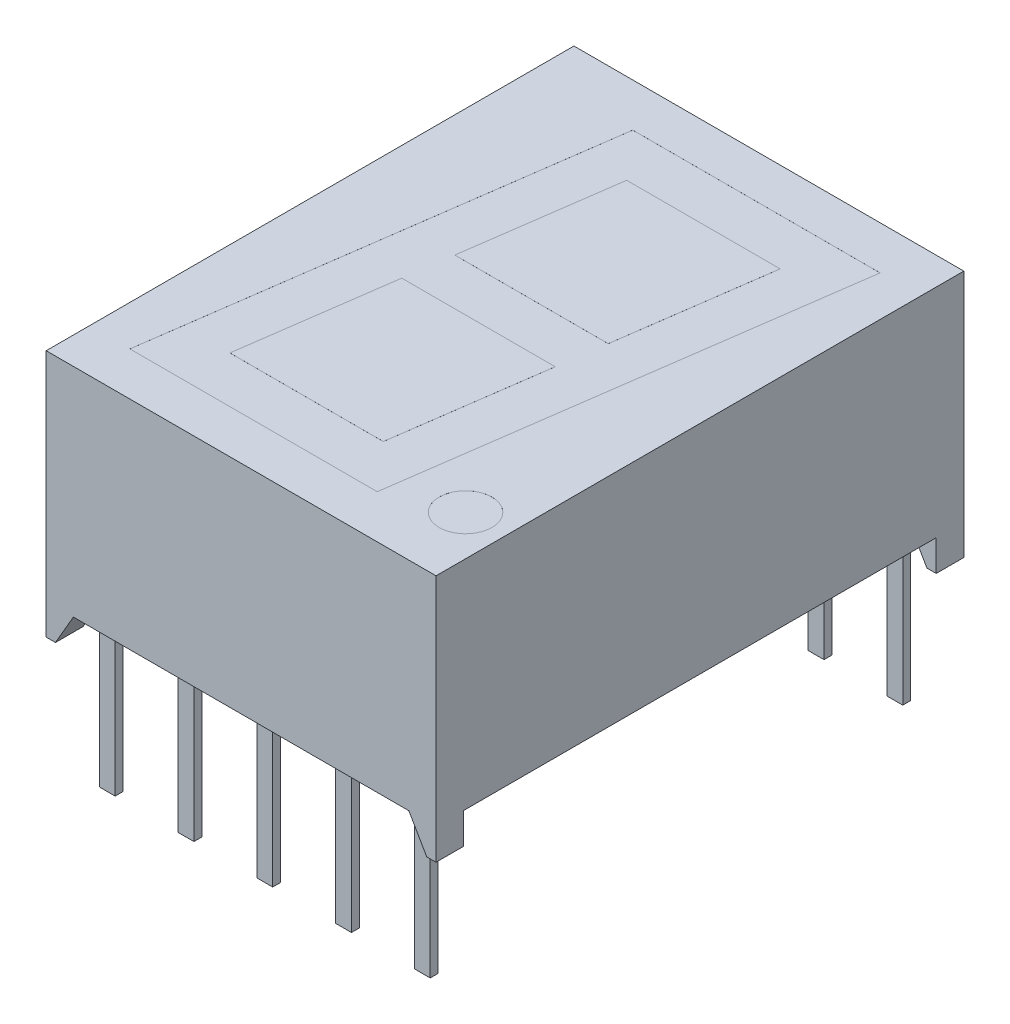
SolidWorks part; units mm, degrees
ref_plane "Plane1" through (0, 0, 0) normal (0, 0, 1) x (1, 0, 0)
ref_plane "Plane2" through (0, 0, 0) normal (0, 1, 0) x (1, 0, 0)
ref_plane "Plane3" through (0, 0, 0) normal (1, 0, 0) x (0, 0, -1)
sketch "Sketch1" plane through (0, 0, 0) normal (1, 0, 0) x (0, 0, -1)
  line L0 (0, 0) -> (0, -7) construction
  line L1 (-8.51, 0) -> (8.51, 0)
  line L2 (-8.51, 0) -> (-8.51, -8)
  line L3 (-8.51, -8) -> (-7.62, -8)
  line L4 (8.51, 0) -> (8.51, -8)
  line L5 (7.62, -8) -> (8.51, -8)
  line L6 (-7.62, -8) -> (-7.62, -7)
  line L7 (-7.62, -7) -> (7.62, -7)
  line L8 (7.62, -8) -> (7.62, -7)
  dimension "D1" = 17.02
  dimension "D2" = 8
  dimension "D3" = 15.24
  dimension "D4" = 1
extrude "Extrude1" add sketch "Sketch1" along normal mid plane 12.573
sketch "Sketch4" plane through (0, 0, 0) normal (0, 1, 0) x (-1, 0, 0)
  line L0 (6.2865, 0) -> (3.9888, 0) construction
  line L1 (6.2865, -8.51) -> (6.2865, 8.51) construction
  line L2 (4.9881, 7.11) -> (2.9896, -7.11)
  line L3 (2.9896, -7.11) -> (-4.9881, -7.11)
  line L4 (-4.9881, -7.11) -> (-2.9896, 7.11)
  line L5 (-2.9896, 7.11) -> (4.9881, 7.11)
  line L6 (3.9888, 0) -> (-3.9888, 0) construction
  line L7 (0, 0) -> (0, 11.7148) construction
  line L8 (-1.6856, 5.61) -> (3.2625, 5.61)
  line L9 (-3.2625, -5.61) -> (-2.5795, -0.75)
  line L10 (1.6856, -5.61) -> (-3.2625, -5.61)
  line L11 (3.2625, 5.61) -> (2.5795, 0.75)
  line L12 (2.5795, 0.75) -> (-2.3687, 0.75)
  line L13 (2.3687, -0.75) -> (-2.5795, -0.75)
  line L14 (-2.3687, 0.75) -> (-1.6856, 5.61)
  line L15 (2.3687, -0.75) -> (1.6856, -5.61)
  line L16 (-4.9881, -7.11) -> (-4.9881, 6.26) construction
  line L17 (0, 50) -> (0, -50) construction
  circle A0 centre (-4.9881, 6.26) radius 0.85
  dimension "D8" = 1.7
  dimension "D1" = 8
  dimension "D2" = 14.22
  dimension "D4" = 7.9
  dimension "D5" = 1.5
  dimension "D6" = 0.75
  dimension "D7" = 0.75
extrude "Cut-Extrude1" cut sketch "Sketch4" against normal blind 0.001
sketch "Sketch5" plane through (0, 0, 0) normal (0, 0, 1) x (1, 0, 0)
  line L0 (-5.9865, -8) -> (-5.4091, -7)
  line L1 (6.2865, -8) -> (-6.2865, -8) construction
  line L2 (-5.4091, -7) -> (5.4091, -7)
  line L3 (5.4091, -7) -> (5.9865, -8)
  line L4 (5.9865, -8) -> (-5.9865, -8)
  line L6 (0, -50) -> (0, 50) construction
  line L7 (-6.2865, 0) -> (-6.2865, -8) construction
  line L8 (6.2865, -7) -> (-6.2865, -7) construction
  point P4 (0, -7)
  dimension "D1" = 0.3
  dimension "D2" = 60
extrude "Cut-Extrude2" cut sketch "Sketch5" against normal through all and the other way through all
sketch "Sketch2" plane through (0, -7, 0) normal (0, -1, 0) x (1, 0, 0)
  line L0 (-0.255, 7.62) -> (-19.5945, 7.62) construction
  line L1 (-0.255, 7.747) -> (0.255, 7.747)
  line L2 (-0.255, 7.747) -> (-0.255, 7.493)
  line L3 (-0.255, 7.493) -> (0.255, 7.493)
  line L4 (0.255, 7.747) -> (0.255, 7.493)
  line L5 (0, 7.747) -> (0, 10.0325) construction
  line L6 (0, 0) -> (6.2512, 0) construction
  line L7 (0.255, -7.747) -> (0.255, -7.493)
  line L8 (-0.255, -7.493) -> (0.255, -7.493)
  line L9 (-0.255, -7.747) -> (-0.255, -7.493)
  line L10 (-0.255, -7.747) -> (0.255, -7.747)
  line L11 (0, -50) -> (0, 50) construction
  dimension "D1" = 0.51
  dimension "D2" = 0.254
  dimension "D3" = 7.62
extrude "Extrude2" add sketch "Sketch2" along normal blind 5.09
pattern_linear "LPattern1" count 3 spacing 2.54 along (1, 0, 0) count 3 spacing 2.54 along (-1, 0, 0) of "Extrude2"
